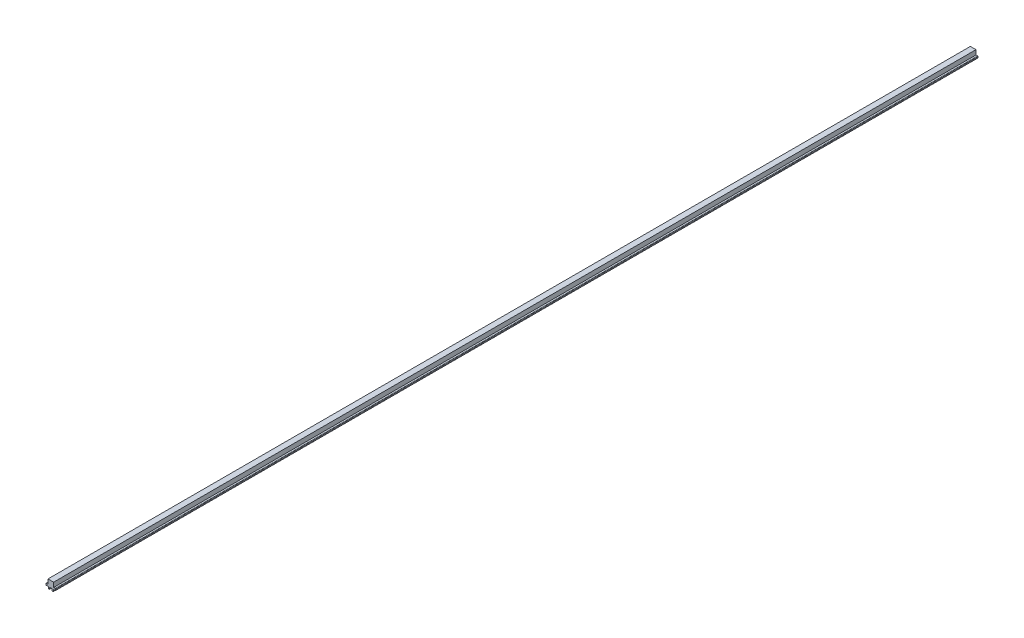
SolidWorks part; units mm, degrees
ref_plane "Front Plane" through (0, 0, 0) normal (0, 0, 1) x (1, 0, 0)
ref_plane "Top Plane" through (0, 0, 0) normal (0, 1, 0) x (1, 0, 0)
ref_plane "Right Plane" through (0, 0, 0) normal (1, 0, 0) x (0, 0, -1)
sketch "Sketch2" plane through (0, 0, 0) normal (0, 0, 1) x (1, 0, 0)
  line L0 (-1.4166, 5.1268) -> (-1.4166, -5.0982) construction
  line L1 (-4.4666, 5.1268) -> (1.6334, 5.1268)
  line L2 (-4.4666, 5.1268) -> (-4.4666, 2.8768)
  line L3 (-4.4666, 2.8768) -> (1.6334, 2.8768)
  line L4 (1.6334, 5.1268) -> (1.6334, 2.8768)
  line L5 (-4.4666, 2.8768) -> (1.6334, 2.8768)
  line L6 (-4.4666, 2.8768) -> (-4.4666, -1.8732)
  line L7 (-4.4666, -1.8732) -> (1.6334, -1.8732)
  line L8 (1.6334, 2.8768) -> (1.6334, -1.8732)
  line L9 (1.6334, 0.1268) -> (3.8334, 0.1268)
  line L10 (1.6334, 0.1268) -> (1.6334, -1.8732)
  line L11 (1.6334, -1.8732) -> (3.8334, -1.8732)
  line L12 (3.8334, 0.1268) -> (3.8334, -1.8732)
  line L13 (-4.4666, -1.8732) -> (-6.6666, -1.8732)
  line L14 (-0.1166, -1.8732) -> (1.3834, -1.8732)
  line L15 (-0.1166, -1.8732) -> (-0.1166, -4.0732)
  line L16 (-0.1166, -4.0732) -> (1.3834, -4.0732)
  line L17 (1.3834, -1.8732) -> (1.3834, -4.0732)
  line L18 (-6.6666, 0.1268) -> (-6.6666, -1.8732)
  line L19 (-4.4666, 0.1268) -> (-6.6666, 0.1268)
  line L20 (-4.4666, 0.1268) -> (-4.4666, -1.8732)
  line L21 (-2.7166, -4.0732) -> (-4.2166, -4.0732)
  line L22 (-4.2166, -1.8732) -> (-4.2166, -4.0732)
  line L23 (-2.7166, -1.8732) -> (-4.2166, -1.8732)
  line L24 (-2.7166, -1.8732) -> (-2.7166, -4.0732)
  dimension "D1" = 6.1
  dimension "D2" = 2.25
  dimension "D3" = 4.75
  dimension "D4" = 2.2
  dimension "D5" = 2
  dimension "D6" = 1.3
  dimension "D7" = 2.2
  dimension "D8" = 1.5
  dimension "D9" = 4.4666
extrude "Boss-Extrude1" add sketch "Sketch2" along normal blind 1000 contours L1 L0 L5 L4 | L0 L3 L6 L7 | L5 L0 L7 L8 | L0 L1 L2 L3 | L12 L9 L8 L11 | L17 L7 L15 L16 | L24 L7 L22 L21 | L6 L19 L18 L13
fillet "Fillet1" radius 0.5 4 edges at (3.8334, -1.8732, 500) (3.8334, 0.1268, 500) (-6.6666, -1.8732, 500) (-6.6666, 0.1268, 500)
fillet "Fillet2" radius 0.5 4 edges at (1.3834, -4.0732, 500) (-0.1166, -4.0732, 500) (-4.2166, -4.0732, 500) (-2.7166, -4.0732, 500)
